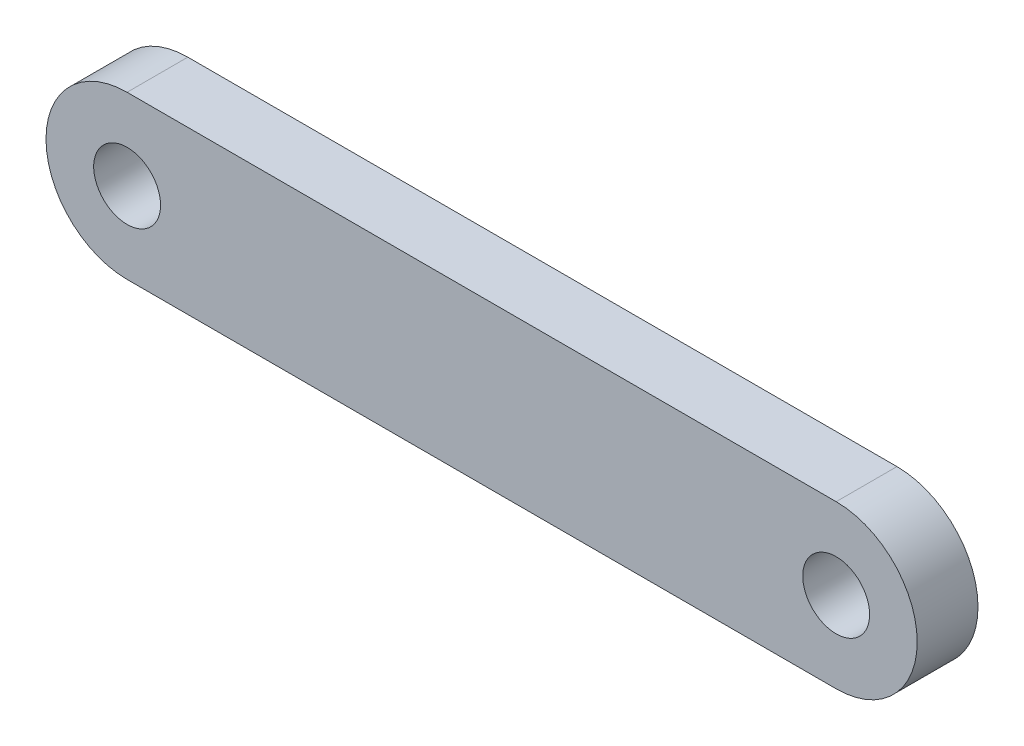
SolidWorks part; units mm, degrees
ref_plane "Front Plane" through (0, 0, 0) normal (0, 0, 1) x (1, 0, 0)
ref_plane "Top Plane" through (0, 0, 0) normal (0, 1, 0) x (1, 0, 0)
ref_plane "Right Plane" through (0, 0, 0) normal (1, 0, 0) x (0, 0, -1)
sketch "Sketch1" plane through (0, 0, 0) normal (0, 0, 1) x (1, 0, 0)
  line L0 (8.9136, -42.8602) -> (43.9136, -42.8602) construction
  line L1 (8.9136, -38.8602) -> (43.9136, -38.8602)
  line L2 (8.9136, -46.8602) -> (43.9136, -46.8602)
  arc A0 (8.9136, -38.8602) -> (8.9136, -46.8602) centre (8.9136, -42.8602) ccw
  arc A1 (43.9136, -46.8602) -> (43.9136, -38.8602) centre (43.9136, -42.8602) ccw
  circle A2 centre (43.9136, -42.8602) radius 1.65
  circle A3 centre (8.9167, -42.8602) radius 1.65
  point P3 (26.4136, -42.8602)
  dimension "D1" = 3.3
  dimension "D2" = 3.3
  dimension "D3" = 8
  dimension "50" = 35
extrude "Boss-Extrude1" add sketch "Sketch1" along normal blind 3
